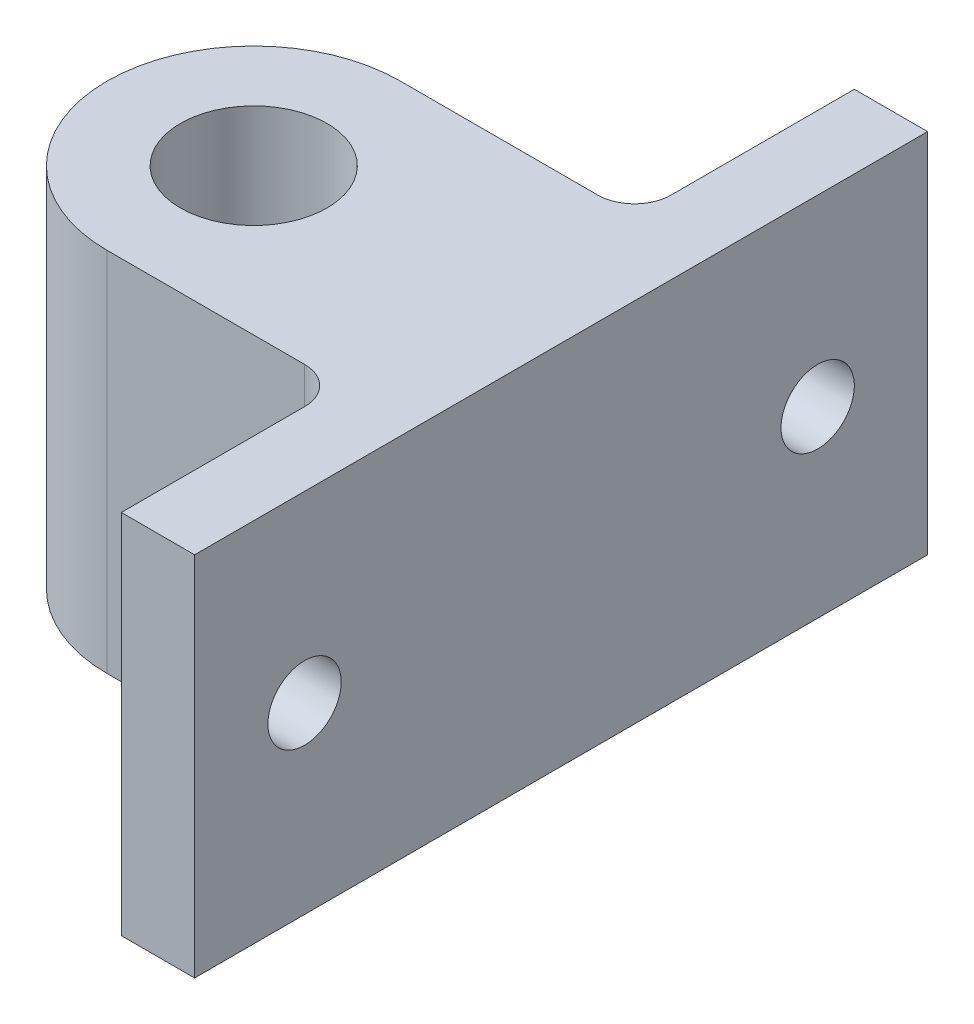
SolidWorks part; units mm, degrees
ref_plane "Front Plane" through (0, 0, 0) normal (0, 0, 1) x (1, 0, 0)
ref_plane "Top Plane" through (0, 0, 0) normal (0, 1, 0) x (1, 0, 0)
ref_plane "Right Plane" through (0, 0, 0) normal (1, 0, 0) x (0, 0, -1)
sketch "Sketch1" plane through (0, 0, 0) normal (0, 1, 0) x (1, 0, 0)
  line L0 (-14.775, 8) -> (-2, 8)
  line L1 (2, -20) -> (-2, -20)
  line L2 (2, -20) -> (2, 20)
  line L3 (2, 20) -> (-2, 20)
  line L4 (-2, -20) -> (-2, -8)
  line L5 (2, -20) -> (-2, 20) construction
  line L6 (2, 20) -> (-2, -20) construction
  line L7 (-2, 8) -> (-2, 20)
  line L8 (-14.775, -8) -> (-2, -8)
  circle A0 centre (-14.775, 0) radius 4
  arc A1 (-14.775, 8) -> (-14.775, -8) centre (-14.775, 0) ccw
  circle A2 centre (-14.775, 0) radius 8 construction
  point P0 (0, 0)
  dimension "D1" = 8
  dimension "D2" = 16.775
  dimension "D3" = 4
  dimension "D4" = 40
  dimension "D5" = 4
extrude "Boss-Extrude1" add sketch "Sketch1" along normal blind 20
sketch "Sketch2" plane through (-2, 0, 0) normal (-1, 0, 0) x (0, 0, 1)
  line L0 (-20, 20) -> (-8, 20) construction
  line L1 (-20, 20) -> (-20, 0) construction
  line L2 (0, 0) -> (0, 20) construction
  line L3 (20, 20) -> (-20, 20) construction
  circle A0 centre (-14, 10) radius 2
  circle A1 centre (14, 10) radius 2
  dimension "D1" = 4
  dimension "D2" = 10
  dimension "D3" = 6
extrude "Cut-Extrude1" cut sketch "Sketch2" against normal blind 20
fillet "Fillet1" radius 2 2 edges at (-2, 10, 8) (-2, 10, -8)
